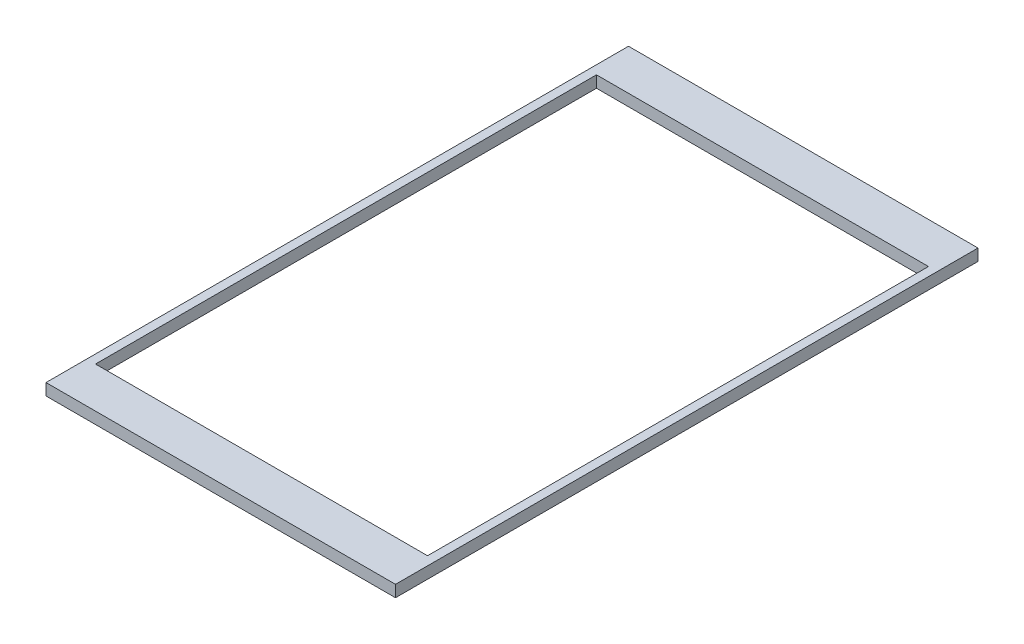
SolidWorks part; units mm, degrees
ref_plane "Front Plane" through (0, 0, 0) normal (0, 0, 1) x (1, 0, 0)
ref_plane "Top Plane" through (0, 0, 0) normal (0, 1, 0) x (1, 0, 0)
ref_plane "Right Plane" through (0, 0, 0) normal (1, 0, 0) x (0, 0, -1)
sketch "Sketch1" plane through (0, 0, 0) normal (0, 1, 0) x (1, 0, 0)
  line L1 (-38.1, -63.5) -> (38.1, -63.5)
  line L2 (-38.1, -63.5) -> (-38.1, 63.5)
  line L3 (-38.1, 63.5) -> (38.1, 63.5)
  line L4 (38.1, -63.5) -> (38.1, 63.5)
  line L5 (-38.1, -63.5) -> (38.1, 63.5) construction
  line L6 (-38.1, 63.5) -> (38.1, -63.5) construction
  point P0 (0, 0)
  dimension "D1" = 76.2
  dimension "D2" = 127
extrude "body" add sketch "Sketch1" along normal blind 2.54
sketch "Sketch2" plane through (0, 2.54, 0) normal (0, 1, 0) x (1, 0, 0)
  line L1 (-36.195, -54.61) -> (36.195, -54.61)
  line L2 (-36.195, -54.61) -> (-36.195, 54.61)
  line L3 (-36.195, 54.61) -> (36.195, 54.61)
  line L4 (36.195, -54.61) -> (36.195, 54.61)
  line L5 (-36.195, -54.61) -> (36.195, 54.61) construction
  line L6 (-36.195, 54.61) -> (36.195, -54.61) construction
  point P0 (0, 0)
  dimension "D1" = 72.39
  dimension "D2" = 0
  dimension "D3" = 109.22
  dimension "D4" = 0
extrude "circuitboard hole" cut sketch "Sketch2" against normal blind 2.54
